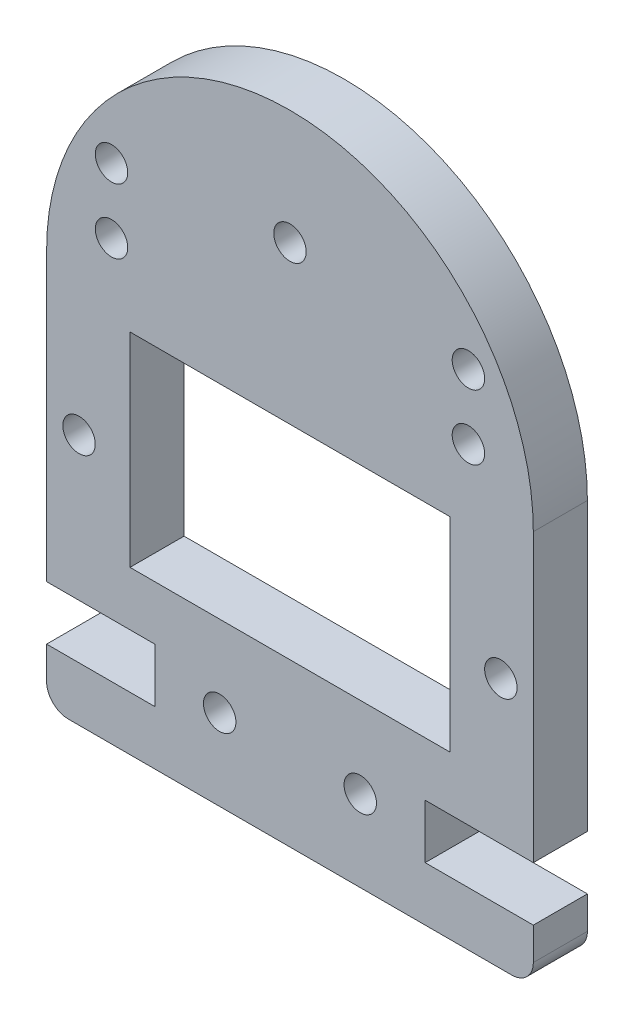
SolidWorks part; units mm, degrees
material "Acrílico (médio-alto impacto)"
ref_plane "Plano frontal" through (0, 0, 0) normal (0, 0, 1) x (1, 0, 0)
ref_plane "Plano superior" through (0, 0, 0) normal (0, 1, 0) x (1, 0, 0)
ref_plane "Plano direito" through (0, 0, 0) normal (1, 0, 0) x (0, 0, -1)
sketch "Esboço8" plane through (0, 0, 0) normal (0, 0, 1) x (1, 0, 0)
  line L0 (-24.2663, -3.25) -> (-24.2663, 13.25)
  line L1 (-14.2663, -13.25) -> (-14.2663, -18.25)
  line L2 (10.7337, -18.25) -> (20.7337, -18.25)
  line L3 (20.7337, -3.2223) -> (20.7337, 13.25)
  line L4 (-14.2663, -13.25) -> (-24.2663, -13.25)
  line L5 (-14.2663, -18.25) -> (-24.2663, -18.25)
  line L6 (20.7337, -3.25) -> (20.7337, -3.2223)
  line L7 (-24.2663, -18.25) -> (-24.2663, -21.25)
  line L9 (-24.2663, -13.25) -> (-24.2663, -3.25)
  line L10 (10.7337, -13.25) -> (20.7337, -13.25)
  line L11 (20.7337, -18.25) -> (20.7337, -21.25)
  line L12 (18.7337, -23.25) -> (-22.2663, -23.25)
  line L17 (10.7337, -13.25) -> (10.7337, -18.25)
  line L18 (20.7337, -13.25) -> (20.7337, -3.25)
  arc A0 (20.7337, 13.25) -> (-24.2663, 13.25) centre (-1.7663, 13.25) ccw
  arc A1 (-24.2663, -21.25) -> (-22.2663, -23.25) centre (-22.2663, -21.25) ccw
  arc A2 (18.7337, -23.25) -> (20.7337, -21.25) centre (18.7337, -21.25) ccw
  point P0 (0, 0)
  dimension "D1" = 2
extrude "Ressalto-extrusão2" add sketch "Esboço8" along normal blind 5
sketch "Esboço9" plane through (0, 0, 0) normal (0, 0, -1) x (-1, 0, 0)
  line L0 (-20.7337, -13.25) -> (-20.7337, 13.25) construction
  line L1 (16.5563, -8.25) -> (-13.0237, -8.25)
  line L2 (16.5563, -8.25) -> (16.5563, 10.6)
  line L3 (16.5563, 10.6) -> (-13.0237, 10.6)
  line L4 (-13.0237, -8.25) -> (-13.0237, 10.6)
  line L5 (24.2663, 13.25) -> (24.2663, -13.25) construction
  line L6 (-10.7337, -13.25) -> (-20.7337, -13.25) construction
  dimension "D1" = 7.71
  dimension "D2" = 7.71
  dimension "D3" = 5
extrude "Corte-extrusão1" cut sketch "Esboço9" against normal blind 5
sketch "Esboço10" plane through (0, 0, 0) normal (0, 0, -1) x (-1, 0, 0)
  line L0 (-10.7337, -13.25) -> (-20.7337, -13.25) construction
  line L1 (-20.7337, -13.25) -> (-20.7337, 13.25) construction
  line L2 (24.2663, 13.25) -> (24.2663, -13.25) construction
  line L3 (24.2663, -13.25) -> (14.2663, -13.25) construction
  circle A0 centre (-17.7337, 0) radius 1.5
  circle A1 centre (21.2663, 0) radius 1.5
  dimension "D1" = 13.25
  dimension "D2" = 3
  dimension "D3" = 3
  dimension "D4" = 13.25
extrude "Corte-extrusão2" cut sketch "Esboço10" against normal blind 5
sketch "Esboço12" plane through (0, 0, 5) normal (0, 0, 1) x (1, 0, 0)
  line L0 (10.7337, -18.25) -> (10.7337, -13.25) construction
  line L1 (-14.2663, -13.25) -> (-14.2663, -18.25) construction
  circle A0 centre (4.7337, -15.75) radius 1.5
  circle A1 centre (-8.2663, -15.75) radius 1.5
  dimension "D1" = 6
  dimension "D2" = 6
extrude "Corte-extrusão3" cut sketch "Esboço12" against normal blind 10
sketch "Esboço13" plane through (0, 0, 5) normal (0, 0, 1) x (1, 0, 0)
  line L1 (20.7337, -13.25) -> (20.7337, 13.25) construction
  arc A1 (20.7337, 13.25) -> (-24.2663, 13.25) centre (-1.7663, 13.25) ccw construction
  circle A2 centre (-1.7663, 25.15) radius 1.5
  point P5 (-1.7663, 35.75)
  dimension "D3" = 22.5
  dimension "D4" = 10.6
extrude "Corte-extrusão4" cut sketch "Esboço13" against normal blind 10
sketch "Esboço14" plane through (0, 0, 5) normal (0, 0, 1) x (1, 0, 0)
  line L0 (-24.2663, -13.25) -> (-14.2663, -13.25) construction
  line L2 (20.7337, -13.25) -> (20.7337, 13.25) construction
  line L3 (-16.5563, 10.6) -> (13.0237, 10.6) construction
  line L4 (-24.2663, 13.25) -> (-24.2663, -13.25) construction
  circle A0 centre (14.7337, 17.25) radius 1.5
  circle A1 centre (14.7337, 23.25) radius 1.5
  circle A2 centre (-18.2663, 23.25) radius 1.5
  circle A3 centre (-18.2663, 17.25) radius 1.5
  point P16 (-19.2663, -13.25)
  dimension "D1" = 6
  dimension "D2" = 6
  dimension "D3" = 6.65
  dimension "D4" = 6
  dimension "D5" = 6
  dimension "D6" = 6
  dimension "D7" = 30.5
extrude "Corte-extrusão5" cut sketch "Esboço14" against normal blind 76
